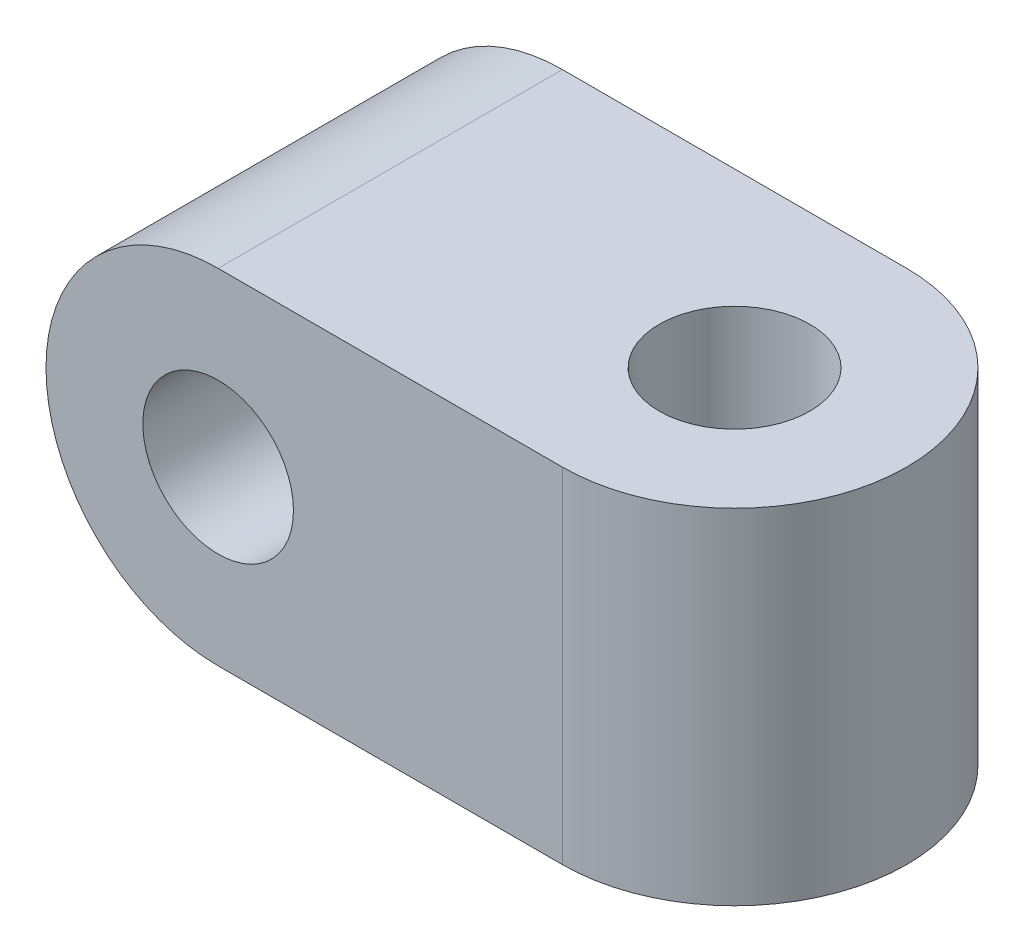
SolidWorks part; units mm, degrees
material "6061 Alloy"
ref_plane "Front Plane" through (0, 0, 0) normal (0, 0, 1) x (1, 0, 0)
ref_plane "Top Plane" through (0, 0, 0) normal (0, 1, 0) x (1, 0, 0)
ref_plane "Right Plane" through (0, 0, 0) normal (1, 0, 0) x (0, 0, -1)
sketch "Sketch1" plane through (0, 0, 0) normal (0, 0, 1) x (1, 0, 0)
  line L1 (-25.4, -12.7) -> (25.4, -12.7)
  line L2 (-25.4, -12.7) -> (-25.4, 12.7)
  line L3 (-25.4, 12.7) -> (25.4, 12.7)
  line L4 (25.4, -12.7) -> (25.4, 12.7)
  line L5 (-25.4, -12.7) -> (25.4, 12.7) construction
  line L6 (-25.4, 12.7) -> (25.4, -12.7) construction
  arc A0 (-12.7, 12.7) -> (-12.7, -12.7) centre (-12.7, 0) ccw
  circle A1 centre (-12.7, 0) radius 5.5562
  point P0 (0, 0)
  dimension "D3" = 11.1125
  dimension "D1" = 25.4
  dimension "D2" = 50.8
extrude "Boss-Extrude1" add sketch "Sketch1" along normal blind 25.4 contours L3 A0 L1 L4 A1
sketch "Sketch2" plane through (0, 12.7, 0) normal (0, 1, 0) x (1, 0, 0)
  line L0 (-12.7, 0) -> (25.4, 0) construction
  line L1 (-12.7, -25.4) -> (25.4, -25.4) construction
  line L2 (25.4, -25.4) -> (25.4, 0) construction
  line L3 (12.7, 0) -> (25.4, 0)
  line L4 (25.4, 0) -> (25.4, -12.7)
  line L5 (25.4, -12.7) -> (25.4, -25.4)
  line L6 (25.4, -25.4) -> (12.7, -25.4)
  arc A0 (12.7, 0) -> (12.7, -25.4) centre (12.7, -12.7) cw
  circle A1 centre (12.7, -12.7) radius 5.5562
  line M1 (25.4, 0) -> (-12.7, 0)
  line M3 (-12.7, -25.4) -> (25.4, -25.4)
  line M4 (25.4, -25.4) -> (25.4, 0)
  dimension "D1" = 11.1125
extrude "Cut-Extrude1" cut sketch "Sketch2" against normal through all both and the other way through all contours A1 | A0 M1 M4 | A0 M4 M3
